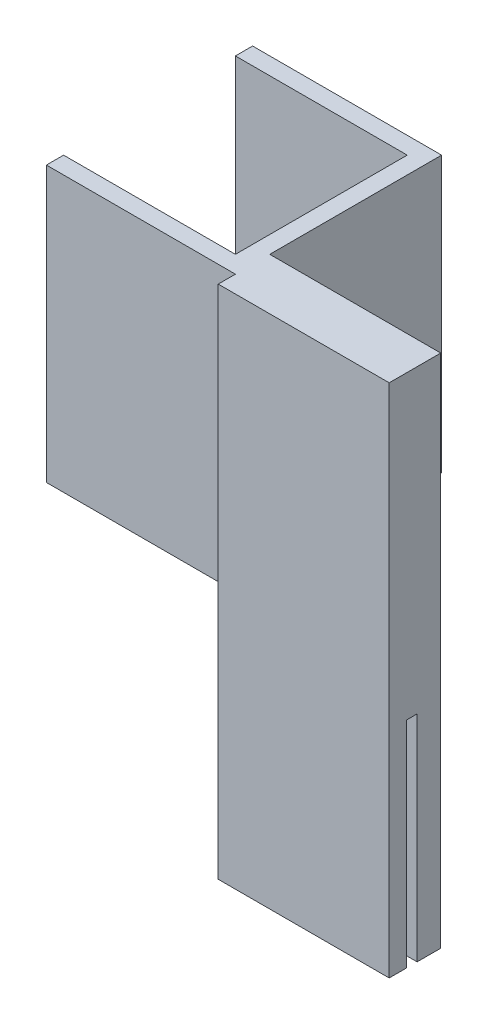
SolidWorks part; units mm, degrees
ref_plane "Front Plane" through (0, 0, 0) normal (0, 0, 1) x (1, 0, 0)
ref_plane "Top Plane" through (0, 0, 0) normal (0, 1, 0) x (1, 0, 0)
ref_plane "Right Plane" through (0, 0, 0) normal (1, 0, 0) x (0, 0, -1)
sketch "Sketch1" plane through (0, 0, 0) normal (0, 1, 0) x (1, 0, 0)
  line L0 (0, 0) -> (-25.4, 0)
  line L2 (0, 0) -> (0, 25.4)
  line L3 (0, 25.4) -> (-25.4, 25.4)
  dimension "D1" = 25.4
extrude "Extrude-Thin1" add sketch "Sketch1" along normal blind 40.64 thin thin type one direction wall 2.54
sketch "Sketch7" plane through (0, 0, 2.54) normal (0, 0, 1) x (1, 0, 0)
  line L0 (2.54, 40.64) -> (27.8144, 40.64)
  line L1 (27.8144, 40.64) -> (27.8144, -35.56)
  line L2 (2.54, -35.56) -> (2.54, 40.64)
  line L3 (2.54, -35.56) -> (27.8144, -35.56)
extrude "Boss-Extrude2" add sketch "Sketch7" along normal blind 2.54 and the other way blind 5.08
sketch "Sketch10" plane through (0, -35.56, 0) normal (0, -1, 0) x (1, 0, 0)
  line L6 (2.54, 2.54) -> (27.8144, 2.54)
  line L7 (27.8144, -2.54) -> (27.8144, 5.08) construction
  line L8 (27.8144, 2.54) -> (27.8144, 0.9529)
  line L9 (27.8144, 0.9529) -> (2.54, 0.9529)
  line L10 (2.54, 2.54) -> (2.54, -2.54) construction
  line L11 (2.54, 0.9529) -> (2.54, 2.54)
extrude "Cut-Extrude10" cut sketch "Sketch10" against normal blind 31.75
